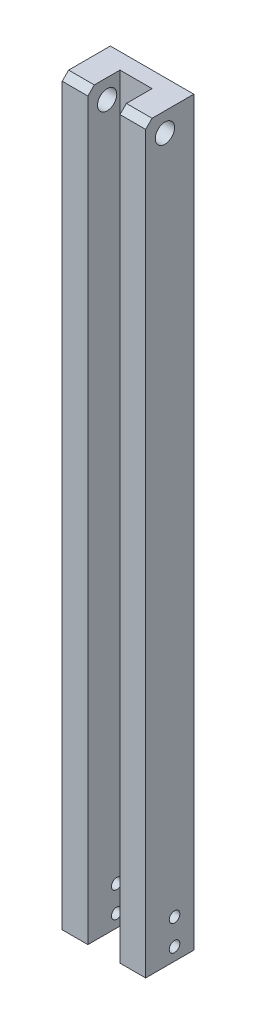
SolidWorks part; units mm, degrees
material "1060 合金"
ref_plane "前视基准面" through (0, 0, 0) normal (0, 0, 1) x (1, 0, 0)
ref_plane "上视基准面" through (0, 0, 0) normal (0, 1, 0) x (1, 0, 0)
ref_plane "右视基准面" through (0, 0, 0) normal (1, 0, 0) x (0, 0, -1)
sketch "草图1" plane through (0, 0, 0) normal (0, 1, 0) x (1, 0, 0)
  line L0 (0, 0) -> (0, -7.2039) construction
  line L1 (-13, -7.5) -> (-5, -7.5)
  line L2 (-13, -7.5) -> (-13, 7.5)
  line L3 (-13, 7.5) -> (13, 7.5)
  line L4 (13, -7.5) -> (13, 7.5)
  line L5 (-13, -7.5) -> (13, 7.5) construction
  line L6 (-13, 7.5) -> (13, -7.5) construction
  line L7 (5, -7.5) -> (13, -7.5)
  line L8 (-5, 2.5) -> (5, 2.5)
  line L9 (-5, 2.5) -> (-5, -7.5)
  line L11 (5, 2.5) -> (5, -7.5)
  line L12 (-5, 2.5) -> (5, -7.5) construction
  line L13 (-5, -7.5) -> (5, 2.5) construction
  point P0 (0, 0)
  point P8 (0, -2.5)
  dimension "D1" = 26
  dimension "D2" = 5
  dimension "D3" = 10
  dimension "D4" = 10
extrude "凸台-拉伸1" add sketch "草图1" against normal blind 231
sketch "草图2" plane through (13, 0, 0) normal (1, 0, 0) x (0, 0, -1)
  line L0 (-7.5, -231) -> (-7.5, 0) construction
  line L2 (-7.5, 0) -> (7.5, 0) construction
  circle A0 centre (-1.5, -6) radius 3
  dimension "D3" = 6
  dimension "D1" = 6
  dimension "D2" = 6
extrude "切除-拉伸1" cut sketch "草图2" against normal through all
sketch "草图3" plane through (0, 0, 0) normal (1, 0, 0) x (0, 0, -1)
  line L0 (1.05, -85) -> (1.05, -186) construction
  line L1 (3.6, -85) -> (3.6, -186)
  line L2 (-1.5, -85) -> (-1.5, -186)
  line L3 (-7.5, -231) -> (7.5, -231) construction
  line L4 (-7.5, 0) -> (7.5, 0) construction
  line L5 (-7.5, -231) -> (-7.5, 0) construction
  arc A0 (3.6, -85) -> (-1.5, -85) centre (1.05, -85) ccw
  arc A1 (-1.5, -186) -> (3.6, -186) centre (1.05, -186) ccw
  point P2 (1.05, -135.5)
  dimension "D1" = 5.1
  dimension "D2" = 45
  dimension "D3" = 85
  dimension "D4" = 6
extrude "切除-拉伸2" [suppressed] cut sketch "草图3" against normal through all both and the other way through all
hole_wizard "M3 螺纹孔1" [suppressed] positions "草图5" profile "草图4" tap size "M3" standard "GB"
sketch "草图5" plane through (0, 0, -8.5) normal (0, 0, -1) x (-1, 0, 0)
  line L3 (0, 0) -> (0, -13.2203) construction
  line L6 (-13, 0) -> (13, 0) construction
  point P0 (0, -6)
  dimension "D1" = 6
sketch "草图4" plane through (0, -6, -8.5) normal (1, 0, 0) x (0, 1, 0)
  line L0 (0, 0) -> (0, 17)
  line L1 (0, 17) -> (1.25, 17)
  line L2 (1.25, 17) -> (1.25, 0)
  line L5 (1.25, 0) -> (0, 0)
  line L11 (0, -6.35) -> (0, 107.95) construction
  dimension "螺纹线主直径" = 2.5
  dimension "通孔螺纹孔钻头深度" = 17
hole_wizard "M4 螺纹孔1" positions "草图7" profile "草图6" tap size "M4" standard "GB" end condition through all
sketch "草图7" plane through (-13, 0, 0) normal (-1, 0, 0) x (0, 0, 1)
  line L0 (-1.5, -236.7827) -> (-1.5, -210.4174) construction
  line L2 (-7.5, -231) -> (-7.5, 0) construction
  line L3 (-7.5, -231) -> (7.5, -231) construction
  point P0 (-1.5, -227)
  point P2 (-1.5, -219)
  dimension "D1" = 8
  dimension "D2" = 6
  dimension "D3" = 4
sketch "草图6" plane through (-13, -227, -1.5) normal (0, 1, 0) x (0, 0, 1)
  line L0 (0, 0) -> (0, 26)
  line L1 (0, 26) -> (1.65, 26)
  line L2 (1.65, 26) -> (1.65, 0)
  line L5 (1.65, 0) -> (0, 0)
  line L11 (0, -6.35) -> (0, 107.95) construction
  dimension "螺纹线主直径" = 3.3
  dimension "通孔螺纹孔钻头深度" = 26
chamfer "倒角1" distance 2 angle 45 2 edges at (9, 0, 7.5) (-9, 0, 7.5)
sketch "草图8" plane through (0, 0, -2.5) normal (0, 0, 1) x (1, 0, 0)
  line L1 (-5, -235.4527) -> (5, -235.4527)
  line L2 (-5, -235.4527) -> (-5, -67.45)
  line L3 (-5, -67.45) -> (5, -67.45)
  line L4 (5, -235.4527) -> (5, -67.45)
  line L5 (-5, -235.4527) -> (5, -67.45) construction
  line L6 (-5, -67.45) -> (5, -235.4527) construction
  line L7 (-5, -231) -> (-5, -2) construction
  line L9 (5, -231) -> (5, -2) construction
  point P0 (0, -151.4514)
extrude "切除-拉伸3" cut sketch "草图8" against normal up to next
